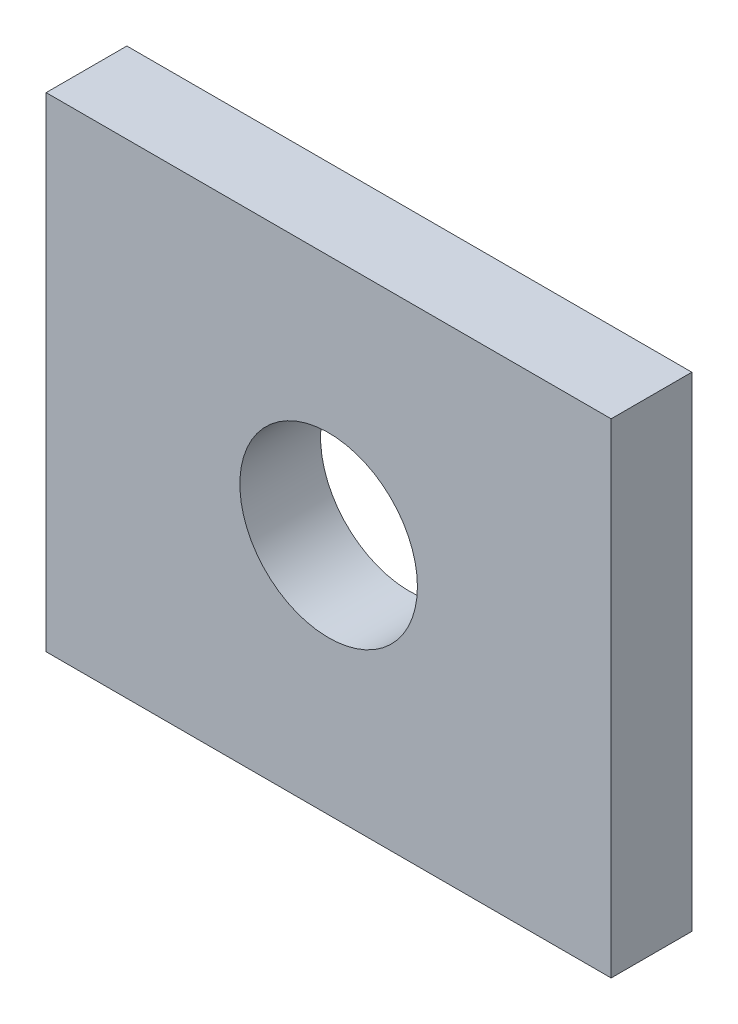
SolidWorks part; units mm, degrees
other "Accelerometer Edge Clamp"
ref_plane "Front Plane" through (0, 0, 0) normal (0, 0, 1) x (1, 0, 0)
ref_plane "Top Plane" through (0, 0, 0) normal (0, 1, 0) x (1, 0, 0)
ref_plane "Right Plane" through (0, 0, 0) normal (1, 0, 0) x (0, 0, -1)
sketch3d "Clamp Outline Sketch datum points"
  point P0 (0, 0, 0)
  point P1 (10, 0, 0)
  point P2 (0, 10, 0)
ref_plane "Clamp Outline Sketch plane" through (0, 0, 0) normal (0, 0, 1) x (1, 0, 0)
sketch "Clamp Outline Sketch" plane through (0, 0, 0) normal (0, 0, 1) x (1, 0, 0)
  line L0 (-3.5, -3) -> (3.5, -3)
  line L1 (3.5, -3) -> (3.5, 3)
  line L2 (3.5, 3) -> (-3.5, 3)
  line L3 (-3.5, 3) -> (-3.5, -3)
extrude "Clamp Outline" add sketch "Clamp Outline Sketch" along normal blind 1 separate body
sketch3d "M2 Clearance Sketch datum points"
  point P0 (0, 0, -0.1)
  point P1 (10, 0, -0.1)
  point P2 (0, 10, -0.1)
ref_plane "M2 Clearance Sketch plane" through (0, 0, -0.1) normal (0, 0, 1) x (1, 0, 0)
sketch "M2 Clearance Sketch" plane through (0, 0, -0.1) normal (0, 0, 1) x (1, 0, 0)
  circle A0 centre (0, 0) radius 1.1
extrude "M2 Clearance" cut sketch "M2 Clearance Sketch" along normal blind 1.2
